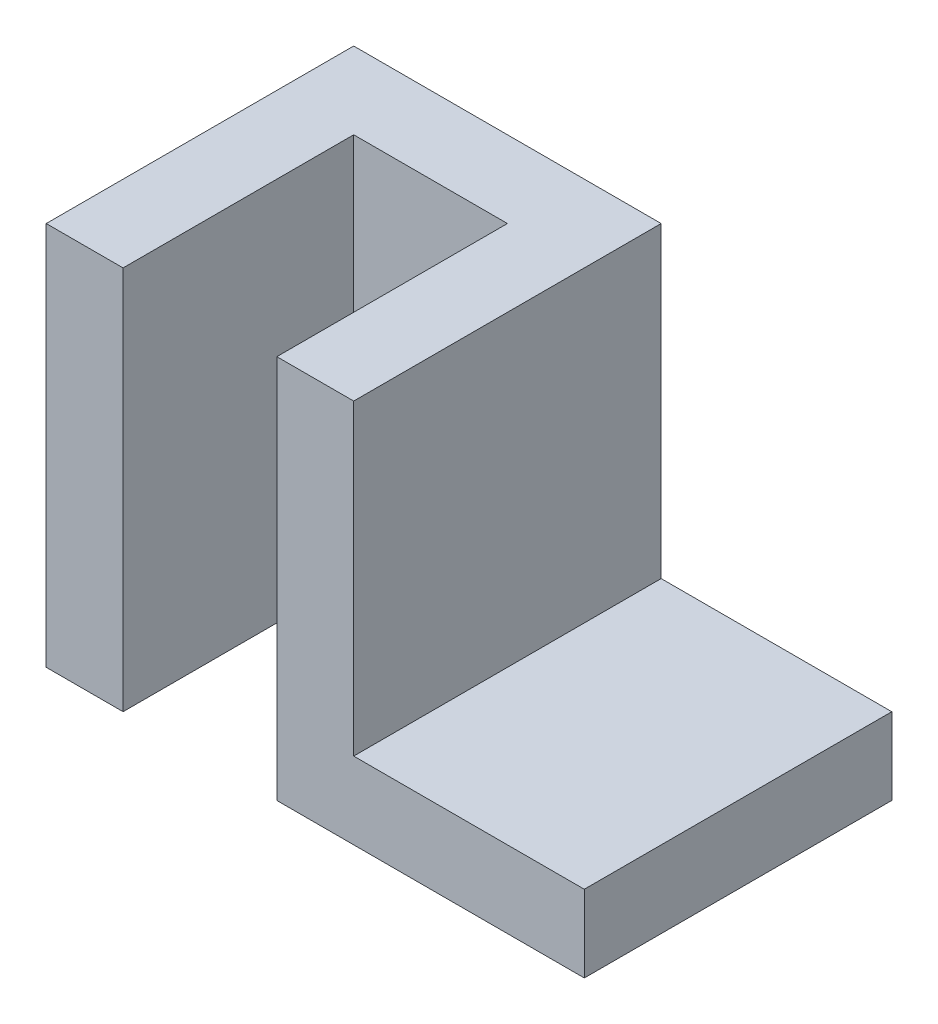
SolidWorks part; units mm, degrees
ref_plane "Front Plane" through (0, 0, 0) normal (0, 0, 1) x (1, 0, 0)
ref_plane "Top Plane" through (0, 0, 0) normal (0, 1, 0) x (1, 0, 0)
ref_plane "Right Plane" through (0, 0, 0) normal (1, 0, 0) x (0, 0, -1)
sketch "Sketch1" plane through (0, 0, 0) normal (0, 1, 0) x (1, 0, 0)
  line L1 (-35, 20) -> (35, 20)
  line L2 (-35, 20) -> (-35, -20)
  line L3 (-35, -20) -> (35, -20)
  line L4 (35, 20) -> (35, -20)
  dimension "D1" = 40
  dimension "D2" = 70
  dimension "D3" = 20
  dimension "D4" = 35
extrude "Boss-Extrude1" add sketch "Sketch1" along normal blind 10
sketch "Sketch2" plane through (0, 10, 0) normal (0, 1, 0) x (1, 0, 0)
  line L0 (-35, -20) -> (35, -20) construction
  line L1 (-35, 20) -> (5, 20)
  line L2 (-35, 20) -> (-35, -20)
  line L3 (-35, -20) -> (5, -20)
  line L4 (5, 20) -> (5, -20)
  dimension "D1" = 40
extrude "Boss-Extrude2" add sketch "Sketch2" along normal blind 40
sketch "Sketch3" plane through (0, 50, 0) normal (0, 1, 0) x (1, 0, 0)
  line L4 (-35, -20) -> (5, -20) construction
  line L5 (-5, -20) -> (-5, 10)
  line L6 (-5, 10) -> (-25, 10)
  line L7 (-25, 10) -> (-25, -20)
  line L9 (-25, -20) -> (-5, -20)
extrude "Cut-Extrude1" cut sketch "Sketch3" against normal through all
